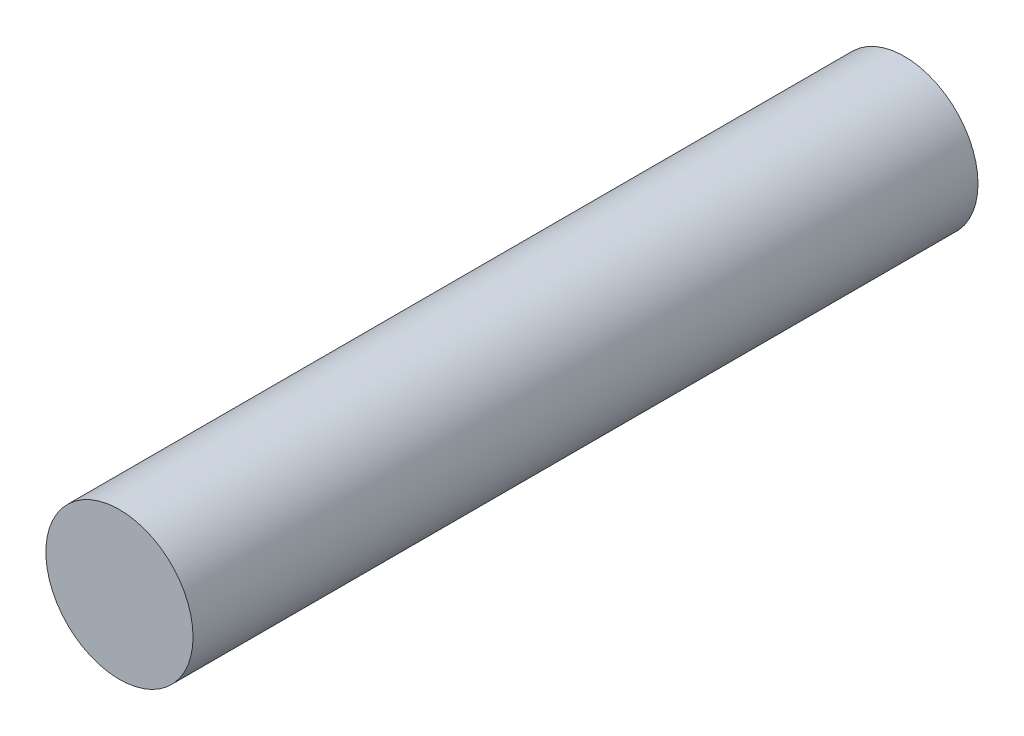
SolidWorks part; units mm, degrees
ref_plane "Front Plane" through (0, 0, 0) normal (0, 0, 1) x (1, 0, 0)
ref_plane "Top Plane" through (0, 0, 0) normal (0, 1, 0) x (1, 0, 0)
ref_plane "Right Plane" through (0, 0, 0) normal (1, 0, 0) x (0, 0, -1)
sketch "Sketch1" plane through (0, 0, 0) normal (0, 0, 1) x (1, 0, 0)
  circle A0 centre (0, 0) radius 3
  dimension "D1" = 6
extrude "Boss-Extrude1" add sketch "Sketch1" along normal blind 32
